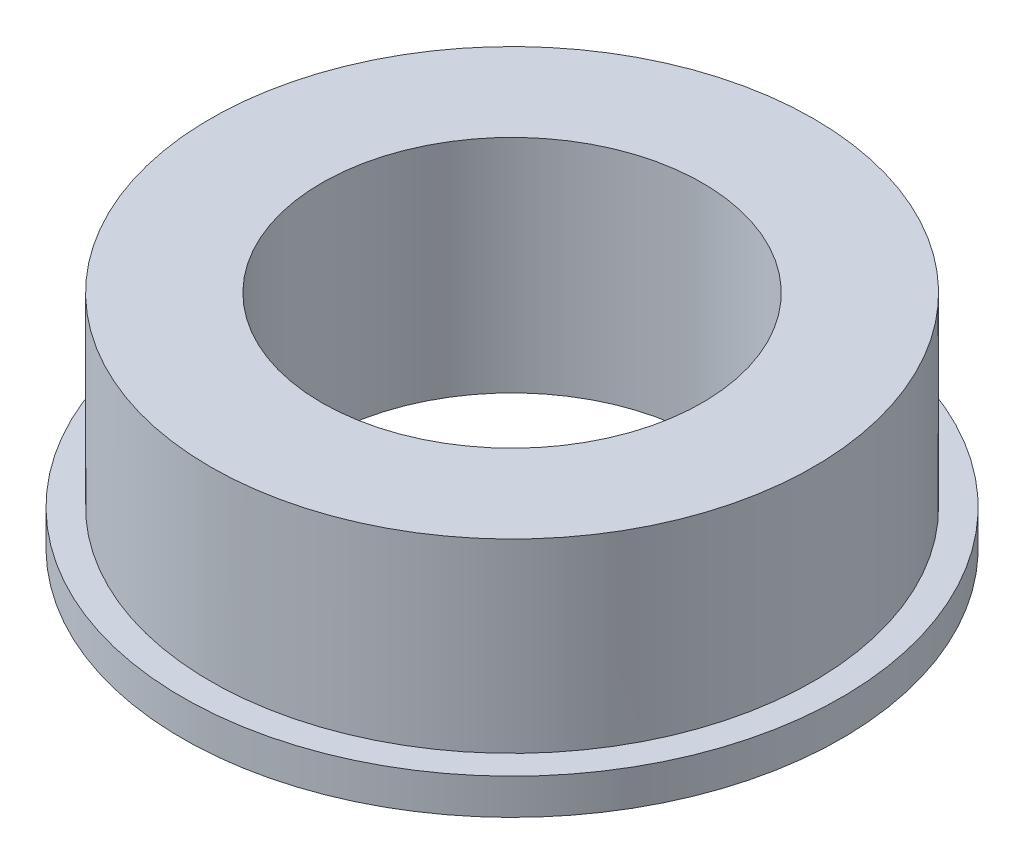
SolidWorks part; units mm, degrees
ref_plane "Front Plane" through (0, 0, 0) normal (0, 0, 1) x (1, 0, 0)
ref_plane "Top Plane" through (0, 0, 0) normal (0, 1, 0) x (1, 0, 0)
ref_plane "Right Plane" through (0, 0, 0) normal (1, 0, 0) x (0, 0, -1)
sketch "Sketch1" plane through (0, 0, 0) normal (0, 1, 0) x (1, 0, 0)
  circle A0 centre (0, 0) radius 6.3373
  circle A1 centre (0, 0) radius 4
  dimension "D1" = 12.6746
  dimension "D2" = 8
extrude "Boss-Extrude1" add sketch "Sketch1" along normal blind 4.65
sketch "Sketch2" plane through (0, 0, 0) normal (0, -1, 0) x (1, 0, 0)
  circle A0 centre (0, 0) radius 4 construction
  circle A1 centre (0, 0) radius 4
  circle A2 centre (0, 0) radius 6.925
  dimension "D1" = 13.85
extrude "Boss-Extrude2" add sketch "Sketch2" against normal blind 0.75
sketch "Sketch3" plane through (0, 0, 0) normal (0, -1, 0) x (1, 0, 0)
  line L0 (0, 0) -> (6.925, 0) construction
  line L1 (6.925, 0) -> (6.925, 14.1202) construction
  circle A0 centre (0, 0) radius 6.925 construction
  point P5 (0, 0)
  point P7 (2.3469, -0.2574)
